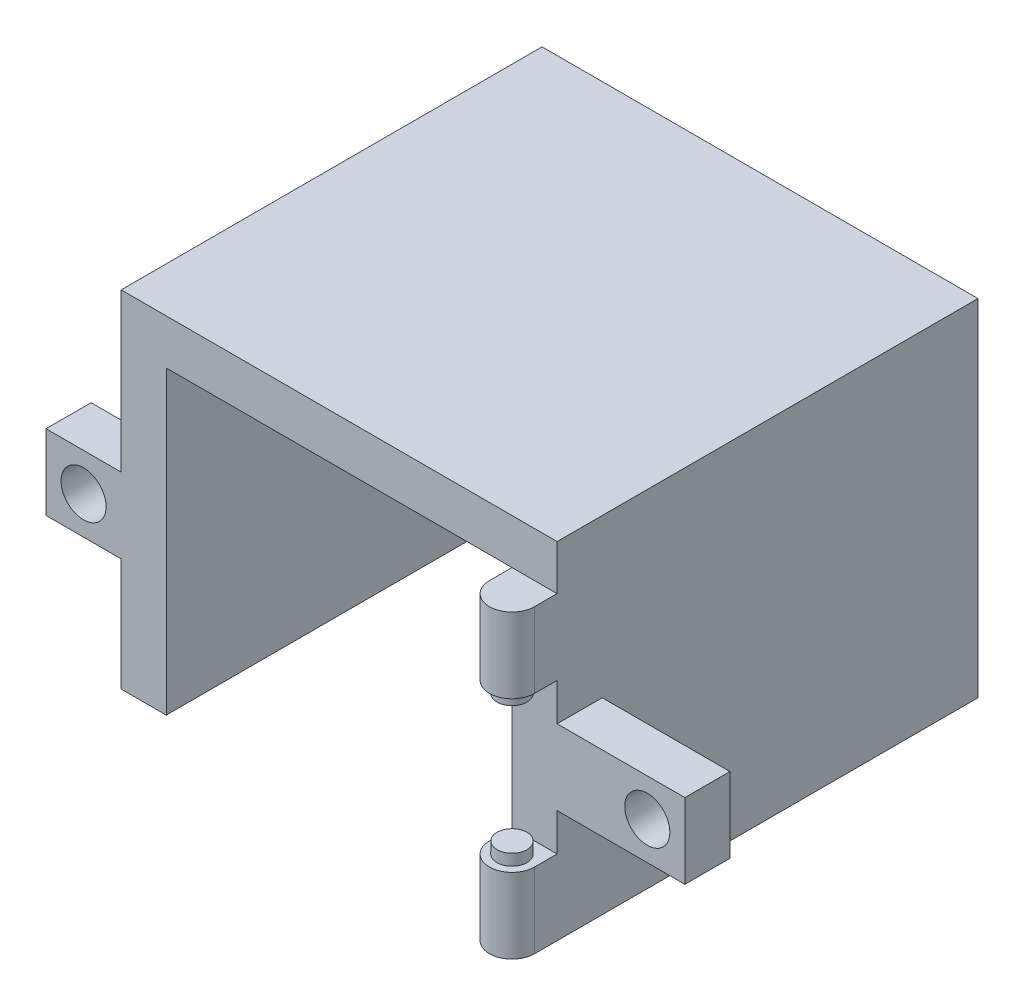
SolidWorks part; units mm, degrees
ref_plane "Alzado" through (0, 0, 0) normal (0, 0, 1) x (1, 0, 0)
ref_plane "Planta" through (0, 0, 0) normal (0, 1, 0) x (1, 0, 0)
ref_plane "Vista lateral" through (0, 0, 0) normal (1, 0, 0) x (0, 0, -1)
sketch "Croquis1" plane through (0, 0, 0) normal (0, 1, 0) x (1, 0, 0)
  line L1 (-14.5, -14) -> (14.5, -14)
  line L2 (-14.5, -14) -> (-14.5, 14)
  line L3 (-14.5, 14) -> (14.5, 14)
  line L4 (14.5, -14) -> (14.5, 14)
  line L5 (-14.5, -14) -> (14.5, 14) construction
  line L6 (-14.5, 14) -> (14.5, -14) construction
  point P0 (0, 0)
  dimension "D1" = 28
  dimension "D2" = 29
extrude "Saliente-Extruir1" add sketch "Croquis1" along normal blind 23
sketch "Croquis2" plane through (0, 0, 14) normal (0, 0, 1) x (1, 0, 0)
  line L0 (-14.5, 0) -> (14.5, 0) construction
  line L1 (-11.5, 20) -> (11.5, 20)
  line L2 (-11.5, 20) -> (-11.5, 0)
  line L3 (-11.5, 0) -> (11.5, 0)
  line L4 (11.5, 20) -> (11.5, 0)
  line L5 (-14.5, 23) -> (-14.5, 0) construction
  line L6 (14.5, 23) -> (14.5, 0) construction
  line L7 (-14.5, 23) -> (14.5, 23) construction
  dimension "D1" = 3
  dimension "D2" = 3
  dimension "D3" = 3
extrude "Cortar-Extruir1" cut sketch "Croquis2" against normal blind 25
sketch "Croquis10" plane through (0, 0, 0) normal (0, -1, 0) x (1, 0, 0)
  line L6 (11.5, 14) -> (14.5, 14)
  line L7 (14.5, 14) -> (14.5, 15.5)
  line L8 (11.5, 14) -> (11.5, 15.5)
  arc A1 (14.5, 15.5) -> (11.5, 15.5) centre (13, 15.5) ccw
  point P1 (0, 0)
  point P2 (13.0794, 15.5)
  point P3 (0, 0)
  dimension "D1" = 1.5
extrude "Saliente-Extruir5" add sketch "Croquis10" against normal blind 5
sketch "Croquis12" plane through (0, 5, 0) normal (0, 1, 0) x (1, 0, 0)
  circle A0 centre (13, -15.5) radius 1
  arc A1 (11.5, -15.5) -> (14.5, -15.5) centre (13, -15.5) ccw construction
  point P3 (10, -15.5)
  dimension "D1" = 2
extrude "Saliente-Extruir7" add sketch "Croquis12" along normal blind 0.75
ref_plane "Plano1" through (0, 10, 0) normal (0, -1, 0) x (-1, 0, 0)
mirror "Simetría1" about plane through (0, 10, 0) normal (0, -1, 0) of "Saliente-Extruir7", "Saliente-Extruir5"
sketch "Croquis13" plane through (0, 0, 14) normal (0, 0, 1) x (1, 0, 0)
  line L5 (18, 12.5) -> (23, 12.5)
  line L7 (18, 7.5) -> (23, 7.5)
  line L8 (23, 12.5) -> (23, 7.5)
  line L11 (18, 12.5) -> (23, 7.5) construction
  line L12 (-15.95, 10) -> (15.95, 10) construction
  line L13 (-19.5, 12.5) -> (-14.5, 12.5)
  line L17 (-19.5, 12.5) -> (-14.5, 7.5) construction
  line L18 (-14.5, 23) -> (-14.5, 0) construction
  line L19 (-14.5, 7.5) -> (-19.5, 7.5)
  line L20 (-19.5, 7.5) -> (-19.5, 12.5)
  line L21 (18, 12.5) -> (14.5, 12.5)
  line L22 (14.5, 15) -> (14.5, 5) construction
  line L23 (18, 7.5) -> (14.5, 7.5)
  line L24 (14.5, 12.5) -> (14.5, 7.5)
  line L25 (-14.5, 12.5) -> (-14.5, 7.5)
  circle A0 centre (20.5, 10) radius 1.5
  circle A1 centre (-17, 10) radius 1.5
  point P9 (20.5, 10)
  point P17 (-17, 10)
  dimension "D2" = 3
  dimension "D4" = 3
  dimension "D1" = 5
  dimension "D3" = 5
  dimension "D5" = 3.5
extrude "Saliente-Extruir8" add sketch "Croquis13" against normal blind 3
